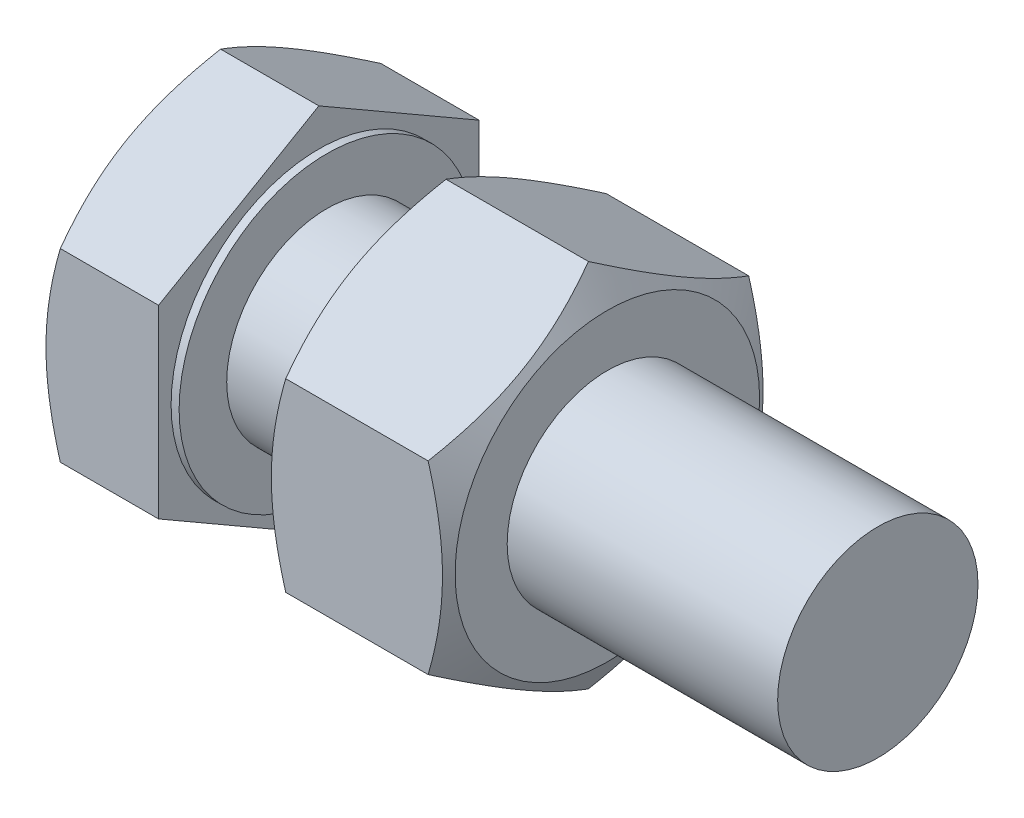
SolidWorks part; units mm, degrees
ref_plane "Спереди" through (0, 0, 0) normal (0, 0, 1) x (1, 0, 0)
ref_plane "Сверху" through (0, 0, 0) normal (0, 1, 0) x (1, 0, 0)
ref_plane "Справа" through (0, 0, 0) normal (1, 0, 0) x (0, 0, -1)
sketch "BoltHeadSk" plane through (0, 0, 0) normal (1, 0, 0) x (0, 0, -1)
  line L1 (0, 18.4752) -> (-16, 9.2376)
  line L2 (-16, 9.2376) -> (-16, -9.2376)
  line L3 (-16, -9.2376) -> (0, -18.4752)
  line L4 (0, -18.4752) -> (16, -9.2376)
  line L5 (16, -9.2376) -> (16, 9.2376)
  line L6 (16, 9.2376) -> (0, 18.4752)
  circle A0 centre (0, 0) radius 16 construction
  dimension "BS" = 32
extrude "BoltHead" add sketch "BoltHeadSk" against normal blind 12.5
sketch "UnBoltHeadSk" plane through (0, 0, 0) normal (0, 0, 1) x (1, 0, 0)
  line L0 (0, 14.75) -> (0, -14.0608) construction
  line L2 (-0.8, 14.75) -> (0, 14.75)
  line L3 (0, 0) -> (-8.3676, 0) construction
  line L4 (0, 18.4752) -> (0, 9.2376) construction
  line L5 (-0.8, 14.75) -> (-0.8, 18.4752)
  line L6 (-12.5, 18.4752) -> (0, 18.4752) construction
  line L7 (-0.8, 18.4752) -> (0, 18.4752)
  line L8 (0, 18.4752) -> (0, 14.75)
  dimension "Bdw" = 29.5
  dimension "Bc" = 0.8
revolve "UNBoltHead" cut sketch "UnBoltHeadSk" angle 360 about L3
sketch "BoltBodySk" plane through (0, 0, 0) normal (1, 0, 0) x (0, 0, -1)
  circle A0 centre (0, 0) radius 10
  dimension "Bd" = 20
extrude "BoltBody" add sketch "BoltBodySk" along normal blind 55
cosmetic thread "BoltThrd" parameters "Lr"=37.5, "Bdr"=18.4
sketch "BoltHCSk" plane through (-12.5, 0, 0) normal (-1, 0, 0) x (0, 0, 1)
  circle A0 centre (0, 0) radius 15.2
  dimension "D1" = 30.4
extrude "BoltHeadChamfer" cut sketch "BoltHCSk" against normal through all draft 60 flip side to cut
sketch "NoToCut" plane through (0, 0, 0) normal (0, 0, 1) x (1, 0, 0)
  line L0 (17.5, 10) -> (17.5, -10)
  line L1 (55, 10) -> (0, 10) construction
  line L2 (0, -10) -> (55, -10) construction
  line L3 (0, -14.75) -> (0, 14.75) construction
ref_plane "NutPlane" through (10, 0, 0) normal (1, 0, 0) x (0, 0, -1)
sketch "NutHeadSk" plane through (10, 0, 0) normal (1, 0, 0) x (0, 0, -1)
  line L1 (-16, 9.2376) -> (-16, -9.2376)
  line L2 (-16, -9.2376) -> (0, -18.4752)
  line L3 (0, -18.4752) -> (16, -9.2376)
  line L4 (16, -9.2376) -> (16, 9.2376)
  line L5 (16, 9.2376) -> (0, 18.4752)
  line L6 (0, 18.4752) -> (-16, 9.2376)
  circle A0 centre (0, 0) radius 16 construction
  circle A1 centre (0, 0) radius 10
  circle A3 centre (0, 0) radius 10 construction
  dimension "Ns" = 32
extrude "NutHead" add sketch "NutHeadSk" along normal blind 18 separate body
ref_plane "NutCenterPlane" through (19, 0, 0) normal (1, 0, 0) x (0, 0, -1)
sketch "NutHCSk" plane through (28, 0, 0) normal (1, 0, 0) x (0, 0, -1)
  circle A0 centre (0, 0) radius 15.2
  circle A1 centre (0, 0) radius 10 construction
  circle M16 centre (0, 0) radius 10
  dimension "D1" = 30.4
extrude "NutHeadChamfer" cut sketch "NutHCSk" against normal through all draft 60 flip side to cut contours A0 M16
mirror "NutHeadChamferMirror" about plane through (19, 0, 0) normal (1, 0, 0) of "NutHeadChamfer"
sketch "UnNutHeadSk" [suppressed] plane through (0, 0, 0) normal (0, 0, 1) x (1, 0, 0)
  line L0 (0, 0) -> (63.0391, 0) construction
  line L1 (10.8, 18.4752) -> (10, 18.4752)
  line L2 (10.8, 18.4752) -> (10.8, 14.75)
  line L3 (10.8, 14.75) -> (10, 14.75)
  line L4 (10, 18.4752) -> (10, 14.75)
  line L5 (0, -16) -> (0, 16) construction
  dimension "Nc" = 0.8
  dimension "Ndw" = 29.5
revolve "UNNutHead" [suppressed] cut sketch "UnNutHeadSk" angle 360 about L0
equation "\"D1@BoltHCSk\" = .95 * \"BS@BoltHeadSk\""
equation "\"Lr@BoltThrd\" = \"Bl@BoltBody\" - \"BLg@NoToCut\""
equation "\"D1@NutHCSk\" = 0.95 * \"Ns@NutHeadSk\""
